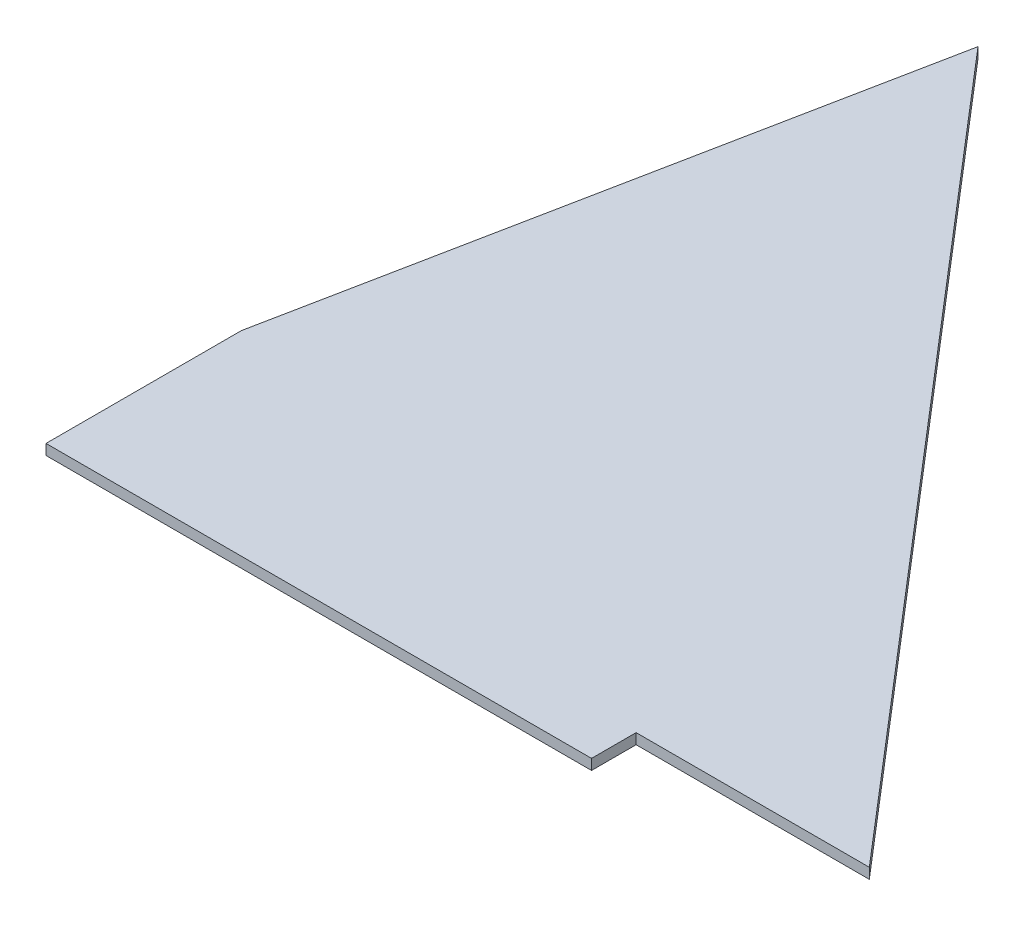
SolidWorks part; units mm, degrees
ref_plane "前视基准面" through (0, 0, 0) normal (0, 0, 1) x (1, 0, 0)
ref_plane "上视基准面" through (0, 0, 0) normal (0, 1, 0) x (1, 0, 0)
ref_plane "右视基准面" through (0, 0, 0) normal (1, 0, 0) x (0, 0, -1)
other "Configuration Table"
sketch "草图1" plane through (0, 0, 0) normal (0, 1, 0) x (1, 0, 0)
  line L0 (0, 0) -> (0, 15.475) construction
  line L1 (0, 15.475) -> (12.0869, 76.1335) construction
  line L2 (12.0869, 76.1335) -> (77.4026, 0) construction
  line L3 (77.4026, 0) -> (0, 0) construction
  line L4 (0, 0) -> (0, -5.25) construction
  line L5 (0, -5.25) -> (54, -5.25) construction
  line L6 (54, -5.25) -> (54, 0) construction
  line L7 (12.666, 73.9227) -> (1, 15.3763)
  line L8 (1, 15.3763) -> (1, -3.25)
  line L9 (1, -3.25) -> (53, -3.25)
  line L10 (53, -3.25) -> (53, 1)
  line L11 (53, 1) -> (75.2271, 1)
  line L12 (75.2271, 1) -> (12.666, 73.9227)
  dimension "D1" = 15.475
  dimension "D2" = 61.851
  dimension "D3" = 100.3118
  dimension "D4" = 77.4026
  dimension "D5" = 5.25
  dimension "D6" = 54
  dimension "D7" = 2
  dimension "D8" = 2
  dimension "D9" = 2
  dimension "D10" = 2
  dimension "D11" = 2
  dimension "D12" = 2
extrude "凸台-拉伸1" add sketch "草图1" along normal blind 1
sketch "草图2" plane through (0, 0, 0) normal (0, 1, 0) x (1, 0, 0)
  line L0 (1, 15.3763) -> (62.8935, 15.3763) construction
  line L1 (75.2271, 1) -> (12.666, 73.9227) construction
  text T0 "UP" font "@Adobe 繁黑體 Std B" height 5
extrude "凸台-拉伸2" add sketch "草图2" against normal blind 1
